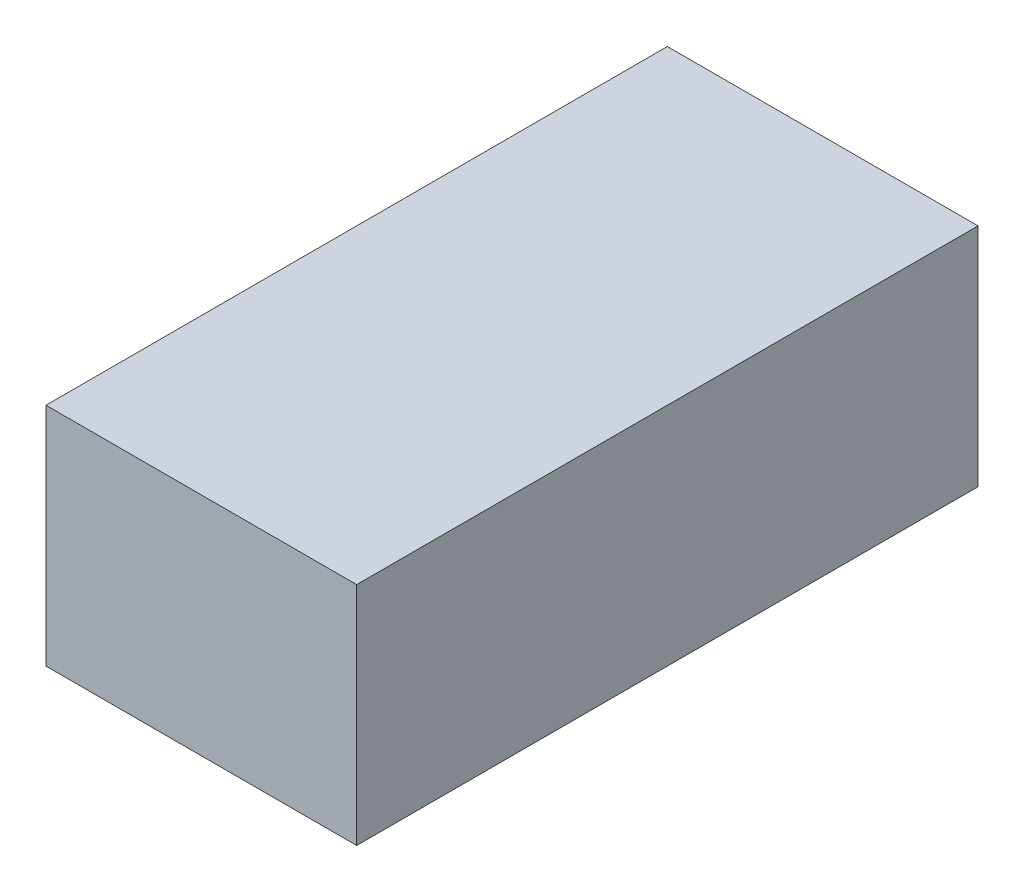
SolidWorks part; units mm, degrees
ref_plane "前视基准面" through (0, 0, 0) normal (0, 0, 1) x (1, 0, 0)
ref_plane "上视基准面" through (0, 0, 0) normal (0, 1, 0) x (1, 0, 0)
ref_plane "右视基准面" through (0, 0, 0) normal (1, 0, 0) x (0, 0, -1)
sketch "草图1" plane through (0, 0, 0) normal (0, 1, 0) x (1, 0, 0)
  line L1 (-27.5, 55) -> (27.5, 55)
  line L2 (-27.5, 55) -> (-27.5, -55)
  line L3 (-27.5, -55) -> (27.5, -55)
  line L4 (27.5, 55) -> (27.5, -55)
  line L5 (-27.5, 55) -> (27.5, -55) construction
  line L6 (-27.5, -55) -> (27.5, 55) construction
  point P0 (0, 0)
  dimension "D1" = 55
  dimension "D2" = 110
extrude "凸台-拉伸1" add sketch "草图1" along normal blind 40
